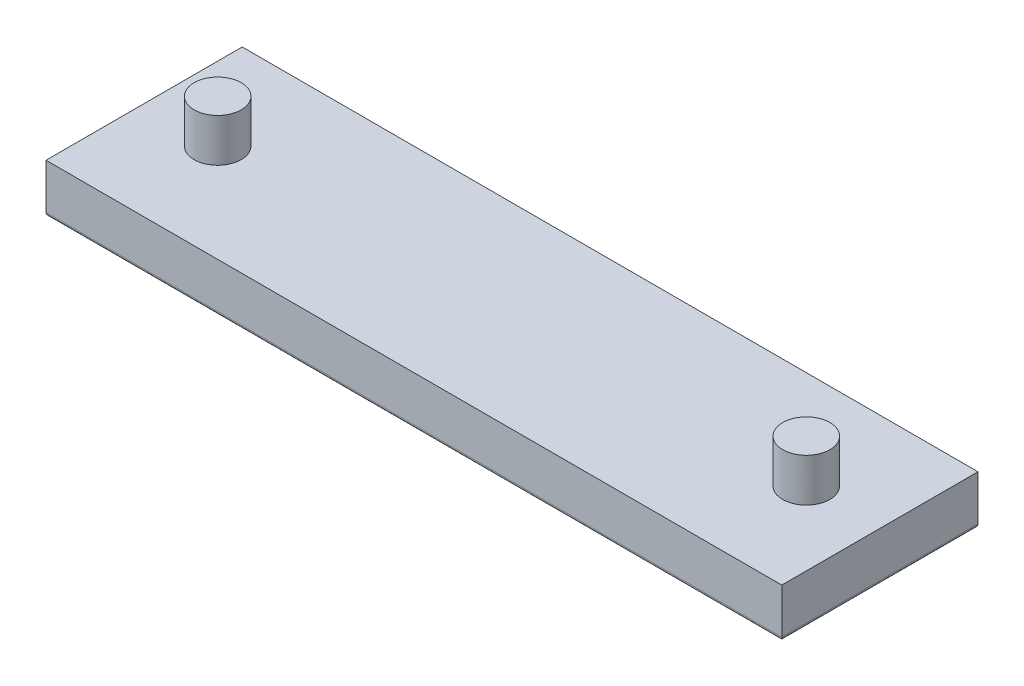
SolidWorks part; units mm, degrees
ref_plane "Front Plane" through (0, 0, 0) normal (0, 0, 1) x (1, 0, 0)
ref_plane "Top Plane" through (0, 0, 0) normal (0, 1, 0) x (1, 0, 0)
ref_plane "Right Plane" through (0, 0, 0) normal (1, 0, 0) x (0, 0, -1)
sketch "Sketch1" plane through (0, 0, 0) normal (0, 1, 0) x (1, 0, 0)
  line L1 (-47.625, -12.7) -> (47.625, -12.7)
  line L2 (-47.625, -12.7) -> (-47.625, 12.7)
  line L3 (-47.625, 12.7) -> (47.625, 12.7)
  line L4 (47.625, -12.7) -> (47.625, 12.7)
  line L5 (-47.625, -12.7) -> (47.625, 12.7) construction
  line L6 (-47.625, 12.7) -> (47.625, -12.7) construction
  point P0 (0, 0)
  dimension "D1" = 95.25
  dimension "D2" = 25.4
extrude "Boss-Extrude1" add sketch "Sketch1" along normal blind 6.35
sketch "Sketch2" plane through (0, 6.35, 0) normal (0, 1, 0) x (1, 0, 0)
  line L2 (-38.1, 0) -> (38.1, 0) construction
  line L4 (47.625, -12.7) -> (47.625, 12.7) construction
  line L5 (47.625, 12.7) -> (-47.625, 12.7) construction
  circle A0 centre (38.1, 0) radius 3.048
  circle A1 centre (-38.1, 0) radius 3.048
  point P4 (0, 0)
  dimension "D2" = 6.096
  dimension "D1" = 6.096
  dimension "D3" = 38.1
extrude "Boss-Extrude2" add sketch "Sketch2" along normal blind 5.588
fillet "Fillet1" radius 0.508 4 edges at (0, 0, -12.7) (-47.625, 0, 0) (0, 0, 12.7) (47.625, 0, 0)
